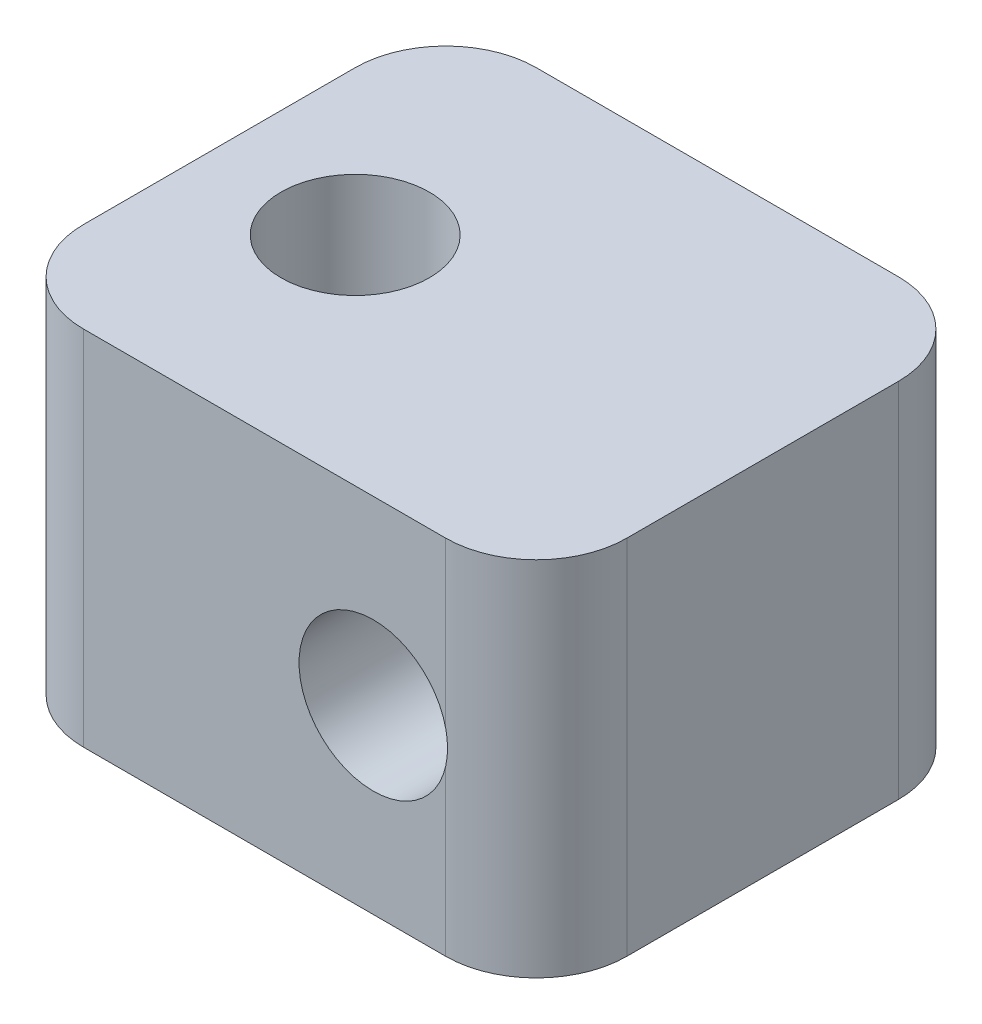
SolidWorks part; units mm, degrees
ref_plane "前视基准面" through (0, 0, 0) normal (0, 0, 1) x (1, 0, 0)
ref_plane "上视基准面" through (0, 0, 0) normal (0, 1, 0) x (1, 0, 0)
ref_plane "右视基准面" through (0, 0, 0) normal (1, 0, 0) x (0, 0, -1)
sketch "草图1" plane through (0, 0, 0) normal (0, 0, 1) x (1, 0, 0)
  line L1 (-15, 10) -> (15, 10)
  line L2 (-15, 10) -> (-15, -10)
  line L3 (-15, -10) -> (15, -10)
  line L4 (15, 10) -> (15, -10)
  line L5 (-15, 10) -> (15, -10) construction
  line L6 (-15, -10) -> (15, 10) construction
  point P0 (0, 0)
  dimension "D1" = 30
  dimension "D2" = 20
extrude "凸台-拉伸1" add sketch "草图1" along normal blind 25
sketch "草图2" plane through (0, 0, 25) normal (0, 0, 1) x (1, 0, 0)
  line L0 (15, -10) -> (15, 10) construction
  circle A0 centre (6, 0) radius 4.1
  dimension "D1" = 8.2
  dimension "D2" = 9
extrude "切除-拉伸1" cut sketch "草图2" against normal blind 25
sketch "草图3" plane through (0, 10, 0) normal (0, 1, 0) x (1, 0, 0)
  line L0 (-15, -25) -> (-15, 0) construction
  line L1 (15, -25) -> (-15, -25) construction
  circle A0 centre (-7, -13) radius 4.1
  dimension "D1" = 8.2
  dimension "D2" = 8
  dimension "D3" = 12
extrude "切除-拉伸2" cut sketch "草图3" against normal blind 25
fillet "圆角2" radius 5 4 edges at (15, 0, 25) (15, 0, 0) (-15, 0, 0) (-15, 0, 25)
